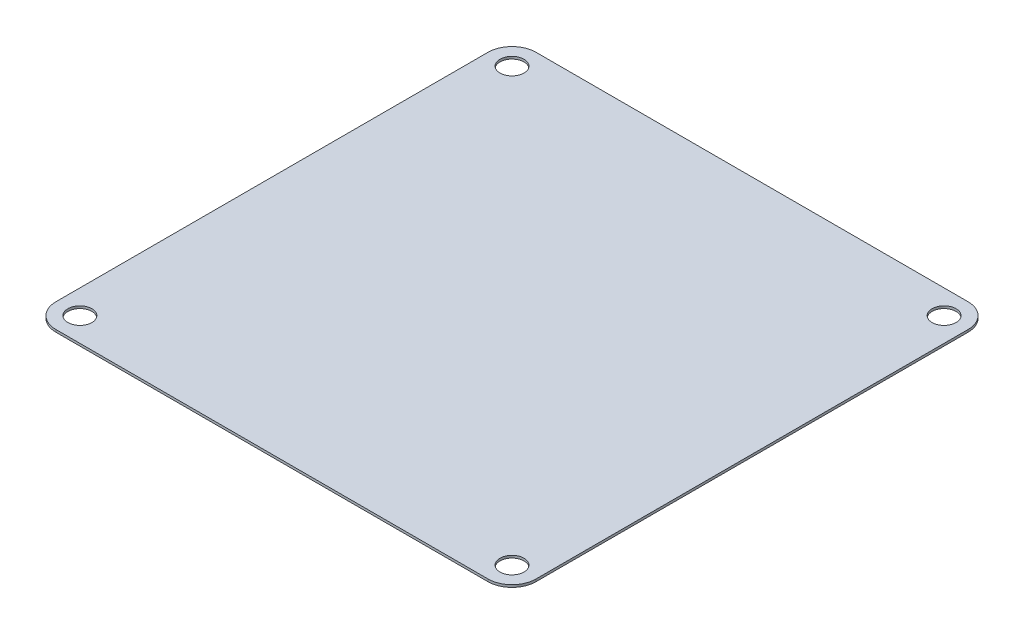
SolidWorks part; units mm, degrees
ref_plane "Front Plane" through (0, 0, 0) normal (0, 0, 1) x (1, 0, 0)
ref_plane "Top Plane" through (0, 0, 0) normal (0, 1, 0) x (1, 0, 0)
ref_plane "Right Plane" through (0, 0, 0) normal (1, 0, 0) x (0, 0, -1)
sketch "Sketch3" plane through (0, 0, 0) normal (0, 1, 0) x (1, 0, 0)
  line L1 (50, -150) -> (-150, -150)
  line L2 (50, -150) -> (50, 50)
  line L3 (50, 50) -> (-150, 50)
  line L4 (-150, -150) -> (-150, 50)
  dimension "D1" = 200
  dimension "D2" = 200
extrude "Boss-Extrude1" add sketch "Sketch3" along normal blind 1
fillet "Fillet1" radius 10 4 edges at (50, 0.5, -50) (50, 0.5, 150) (-150, 0.5, 150) (-150, 0.5, -50)
sketch "Sketch4" plane through (0, 1, 0) normal (0, 1, 0) x (1, 0, 0)
  circle A0 centre (-140, 40) radius 5
  circle A1 centre (40, 40) radius 5
  circle A2 centre (-140, -140) radius 5
  circle A3 centre (40, -140) radius 5
extrude "Cut-Extrude1" cut sketch "Sketch4" against normal blind 10
